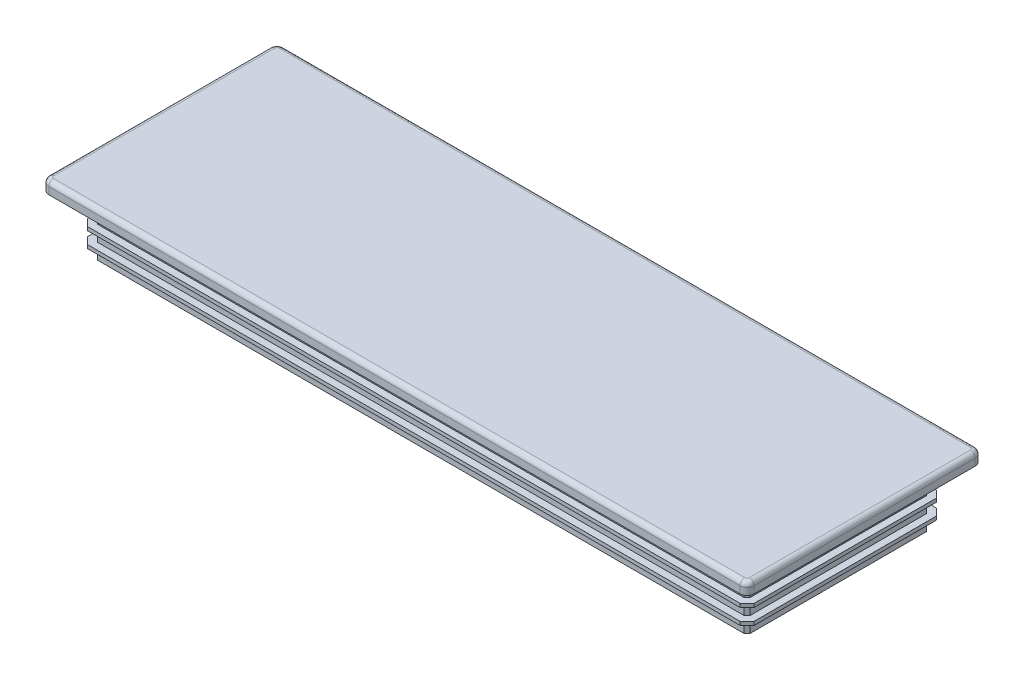
SolidWorks part; units mm, degrees
material "ABS"
ref_plane "Front" through (0, 0, 0) normal (0, 0, 1) x (1, 0, 0)
ref_plane "Top" through (0, 0, 0) normal (0, 1, 0) x (1, 0, 0)
ref_plane "Right" through (0, 0, 0) normal (1, 0, 0) x (0, 0, -1)
sketch "Sketch5" plane through (0, 0, 0) normal (0, 0, 1) x (1, 0, 0)
  line L0 (0, 0) -> (0, 12.7) construction
  dimension "Height" = 12.7
sketch "Sketch1" plane through (0, 0, 0) normal (0, 1, 0) x (1, 0, 0)
  line L1 (-72.009, 21.209) -> (72.009, 21.209)
  line L2 (-72.009, 21.209) -> (-72.009, -21.209)
  line L3 (-72.009, -21.209) -> (72.009, -21.209)
  line L4 (72.009, 21.209) -> (72.009, -21.209)
  line L5 (-72.009, 21.209) -> (72.009, -21.209) construction
  line L6 (-72.009, -21.209) -> (72.009, 21.209) construction
  line L21 (76.2, 25.4) -> (-76.2, 25.4) construction
  line L22 (76.2, 25.4) -> (76.2, -25.4) construction
  line L23 (76.2, -25.4) -> (-76.2, -25.4) construction
  line L24 (-76.2, 25.4) -> (-76.2, -25.4) construction
  line L25 (76.2, 25.4) -> (-76.2, -25.4) construction
  line L26 (76.2, -25.4) -> (-76.2, 25.4) construction
  point P0 (0, 0)
  point P6 (0, 0)
  point P11 (0, 0)
  point P22 (0, 0)
  dimension "D1" = 4.191
  dimension "Head Length" = 152.4
  dimension "Head Width" = 50.8
  dimension "D2" = 4.191
extrude "Boss-Extrude1" add sketch "Sketch1" along normal up to vertex (12.7 mm away) up to point (0, 12.7, 0)
sketch "Sketch2" plane through (0, 12.7, 0) normal (0, 1, 0) x (1, 0, 0)
  line L0 (-76.2, 25.4) -> (-76.2, -25.4) construction
  line L1 (76.2, 25.4) -> (-76.2, 25.4) construction
  line L2 (76.2, 25.4) -> (76.2, -25.4) construction
  line L3 (76.2, -25.4) -> (-76.2, -25.4) construction
  line L4 (-76.2, 23.876) -> (-76.2, -23.876)
  line L5 (74.676, 25.4) -> (-74.676, 25.4)
  line L6 (76.2, 23.876) -> (76.2, -23.876)
  line L7 (74.676, -25.4) -> (-74.676, -25.4)
  arc A0 (-76.2, -23.876) -> (-74.676, -25.4) centre (-74.676, -23.876) ccw
  arc A1 (76.2, -23.876) -> (74.676, -25.4) centre (74.676, -23.876) cw
  arc A2 (74.676, 25.4) -> (76.2, 23.876) centre (74.676, 23.876) cw
  arc A3 (-76.2, 23.876) -> (-74.676, 25.4) centre (-74.676, 23.876) cw
  dimension "D1" = 1.524
extrude "Boss-Extrude2" add sketch "Sketch2" along normal blind 2.54
chamfer "Chamfer1" distance 1.524 angle 45 4 edges at (72.009, 6.35, -21.209) (72.009, 6.35, 21.209) (-72.009, 6.35, -21.209) (-72.009, 6.35, 21.209)
shell "Shell1" thickness 2.54
sketch "Sketch3" plane through (0, 0, 0) normal (0, -1, 0) x (-1, 0, 0)
  line L4 (-72.009, 19.685) -> (-72.009, -19.685)
  line L5 (-72.009, 19.685) -> (-72.009, -19.685)
  line L6 (-70.485, -21.209) -> (70.485, -21.209)
  line L7 (-70.485, -21.209) -> (70.485, -21.209)
  line L8 (72.009, -19.685) -> (72.009, 19.685)
  line L9 (72.009, -19.685) -> (72.009, 19.685)
  line L10 (70.485, 21.209) -> (-70.485, 21.209)
  line L11 (70.485, 21.209) -> (-70.485, 21.209)
  line L16 (-70.485, 21.209) -> (-72.009, 19.685)
  line L17 (-70.485, 21.209) -> (-72.009, 19.685)
  line L18 (-72.009, -19.685) -> (-70.485, -21.209)
  line L19 (-72.009, -19.685) -> (-70.485, -21.209)
  line L20 (70.485, -21.209) -> (72.009, -19.685)
  line L21 (70.485, -21.209) -> (72.009, -19.685)
  line L22 (72.009, 19.685) -> (70.485, 21.209)
  line L23 (72.009, 19.685) -> (70.485, 21.209)
  dimension "D1" = 0
sketch "Sketch4" plane through (0, 0, 0) normal (0, 0, 1) x (1, 0, 0)
  line L1 (72.009, 2.6035) -> (70.485, 2.6035)
  line L2 (72.009, 2.6035) -> (72.009, 0)
  line L3 (72.009, 0) -> (70.485, 0)
  line L4 (70.485, 2.6035) -> (70.485, 0)
  line L5 (76.2, 0) -> (-76.2, 0) construction
  line L6 (-74.676, 12.7) -> (74.676, 12.7) construction
  line L7 (72.009, 9.3345) -> (70.485, 9.3345)
  line L8 (72.009, 9.3345) -> (72.009, 6.731)
  line L9 (72.009, 6.731) -> (70.485, 6.731)
  line L10 (70.485, 9.3345) -> (70.485, 6.731)
  line L11 (72.009, 10.0965) -> (70.485, 10.0965)
  line L12 (72.009, 10.0965) -> (72.009, 12.7)
  line L13 (72.009, 12.7) -> (70.485, 12.7)
  line L14 (70.485, 10.0965) -> (70.485, 12.7)
  line L15 (72.009, 10.0965) -> (72.009, 9.3345) construction
  line L16 (70.485, 5.969) -> (72.009, 5.969)
  line L17 (70.485, 5.969) -> (70.485, 3.3655)
  line L18 (70.485, 3.3655) -> (72.009, 3.3655)
  line L19 (72.009, 5.969) -> (72.009, 3.3655)
  line L20 (72.009, 6.731) -> (72.009, 5.969) construction
  line L21 (72.009, 3.3655) -> (72.009, 2.6035) construction
  line L22 (72.009, 12.7) -> (72.009, 0) construction
  line L23 (74.676, 12.7) -> (76.2, 12.7) construction
  line L26 (70.485, 0) -> (70.485, 12.7) construction
  dimension "D1" = 0.762
sweep "Cut-Sweep2" cut profiles "Sketch4" path "Sketch3"
fillet "Fillet2" radius 1.016 8 edges at (-76.2, 15.24, 0) (-75.7536, 15.24, -24.9536) (0, 15.24, -25.4) (75.7536, 15.24, -24.9536) (76.2, 15.24, 0) (75.7536, 15.24, 24.9536) (0, 15.24, 25.4) (-75.7536, 15.24, 24.9536)
